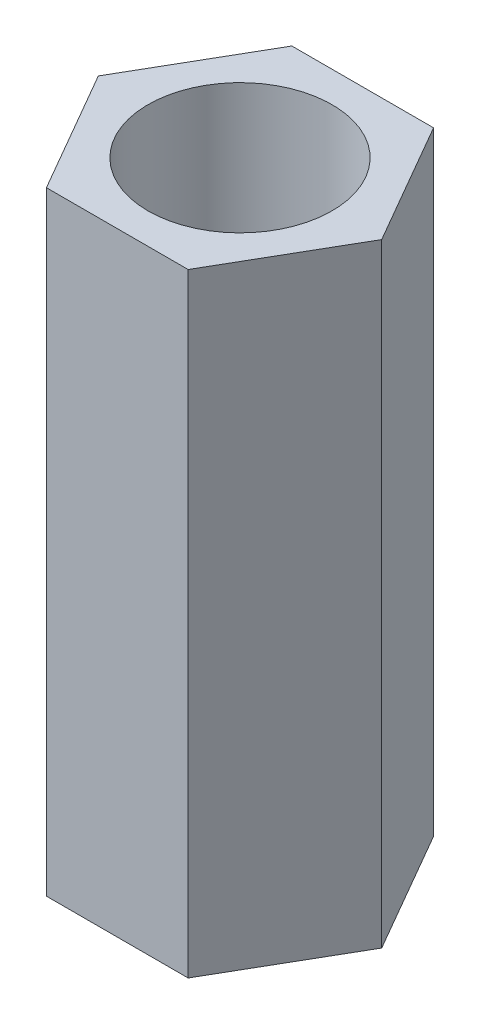
SolidWorks part; units mm, degrees
ref_plane "前视基准面" through (0, 0, 0) normal (0, 0, 1) x (1, 0, 0)
ref_plane "上视基准面" through (0, 0, 0) normal (0, 1, 0) x (1, 0, 0)
ref_plane "右视基准面" through (0, 0, 0) normal (1, 0, 0) x (0, 0, -1)
sketch "草图1" plane through (0, 0, 0) normal (0, 1, 0) x (1, 0, 0)
  line L1 (2.3094, 0) -> (1.1547, 2)
  line L2 (1.1547, 2) -> (-1.1547, 2)
  line L3 (-1.1547, 2) -> (-2.3094, 0)
  line L4 (-2.3094, 0) -> (-1.1547, -2)
  line L5 (-1.1547, -2) -> (1.1547, -2)
  line L6 (1.1547, -2) -> (2.3094, 0)
  circle A0 centre (0, 0) radius 2 construction
  dimension "D1" = 4
extrude "凸台-拉伸1" add sketch "草图1" along normal blind 10
sketch "草图2" plane through (0, 10, 0) normal (0, 1, 0) x (1, 0, 0)
  circle A0 centre (0, 0) radius 1.5
  dimension "D1" = 3
extrude "切除-拉伸1" cut sketch "草图2" against normal blind 10
